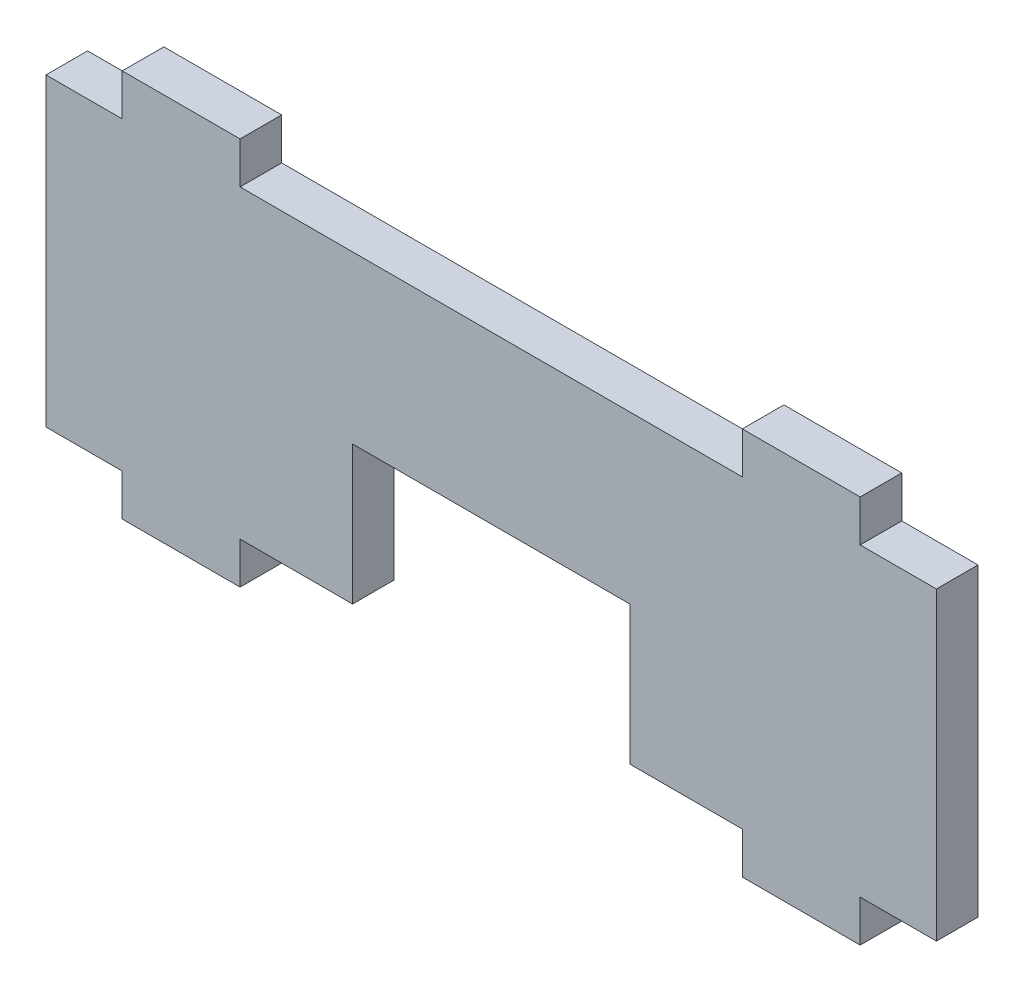
SolidWorks part; units mm, degrees
material "Balsa"
ref_plane "Alzado" through (0, 0, 0) normal (0, 0, 1) x (1, 0, 0)
ref_plane "Planta" through (0, 0, 0) normal (0, 1, 0) x (1, 0, 0)
ref_plane "Vista lateral" through (0, 0, 0) normal (1, 0, 0) x (0, 0, -1)
sketch "Croquis1" plane through (0, 0, 0) normal (0, 0, 1) x (1, 0, 0)
  line L1 (3, 0) -> (8.5, 0)
  line L3 (3, 22) -> (8.5, 22)
  line L6 (8.5, 0) -> (8.5, -3)
  line L7 (8.5, -3) -> (17, -3)
  line L8 (17, 0) -> (17, -3)
  line L14 (53.23, 0) -> (53.23, -3)
  line L15 (53.23, -3) -> (61.73, -3)
  line L16 (61.73, 0) -> (61.73, -3)
  line L18 (61.73, 0) -> (67.23, 0)
  line L19 (3, 11) -> (67.23, 11) construction
  line L20 (61.73, 22) -> (61.73, 25)
  line L21 (53.23, 22) -> (53.23, 25)
  line L24 (17, 22) -> (17, 25)
  line L25 (8.5, 22) -> (8.5, 25)
  line L26 (53.23, 25) -> (61.73, 25)
  line L28 (8.5, 25) -> (17, 25)
  line L31 (61.73, 22) -> (67.23, 22)
  line L32 (17, 22) -> (53.23, 22)
  line L33 (17, 0) -> (25.115, 0)
  line L34 (35.115, 22) -> (35.115, 0) construction
  line L35 (45.115, 0) -> (53.23, 0)
  line L37 (25.115, 0) -> (25.115, 10)
  line L38 (25.115, 10) -> (45.115, 10)
  line L39 (45.115, 0) -> (45.115, 10)
  line L40 (3, 22) -> (3, 0)
  line L41 (67.23, 22) -> (67.23, 0)
  dimension "D3" = 3
  dimension "D4" = 3
  dimension "D5" = 8.5
  dimension "D6" = 8.5
  dimension "D8" = 20
  dimension "D10" = 18.115
  dimension "D11" = 10
extrude "Saliente-Extruir1" add sketch "Croquis1" along normal blind 3
